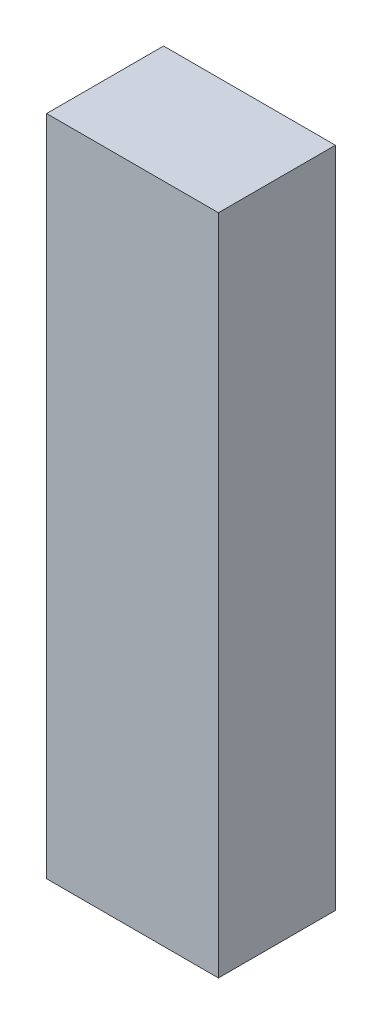
SolidWorks part; units mm, degrees
ref_plane "Front" through (0, 0, 0) normal (0, 0, 1) x (1, 0, 0)
ref_plane "Top" through (0, 0, 0) normal (0, 1, 0) x (1, 0, 0)
ref_plane "Right" through (0, 0, 0) normal (1, 0, 0) x (0, 0, -1)
sketch "Sketch1" plane through (0, 0, 0) normal (0, 0, 1) x (1, 0, 0)
  line L1 (0, 0) -> (14, 0)
  line L2 (0, 0) -> (0, -54)
  line L3 (0, -54) -> (14, -54)
  line L4 (14, 0) -> (14, -54)
  dimension "D1" = 54
  dimension "D3" = 14
extrude "Boss-Extrude1" add sketch "Sketch1" against normal blind 9.53
